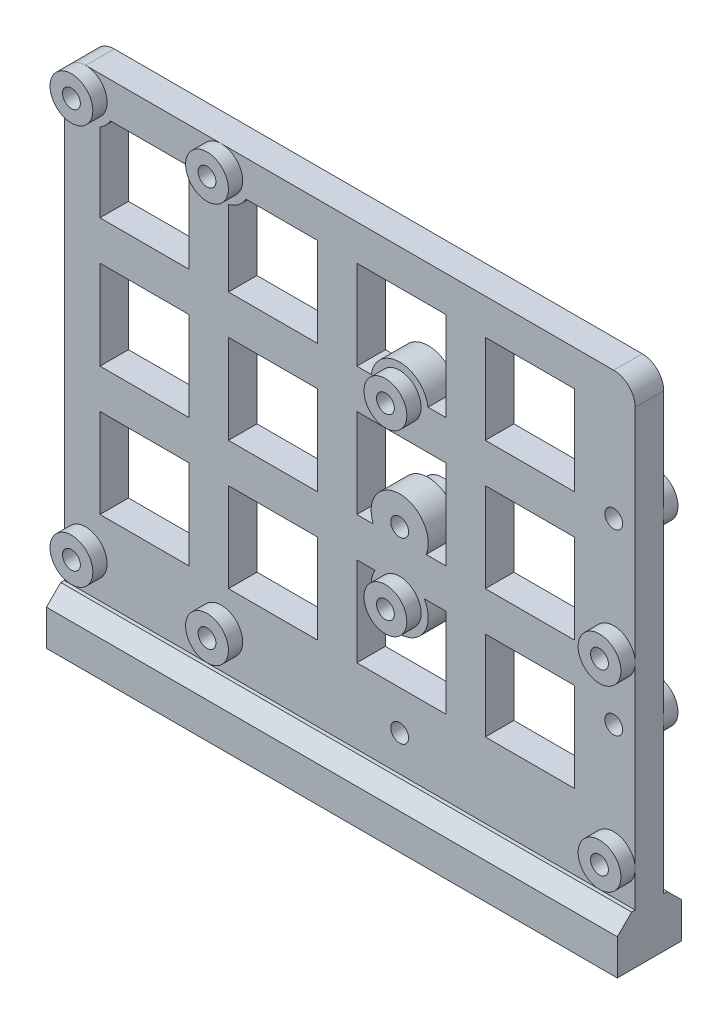
SolidWorks part; units mm, degrees
ref_plane "Спереди" through (0, 0, 0) normal (0, 0, 1) x (1, 0, 0)
ref_plane "Сверху" through (0, 0, 0) normal (0, 1, 0) x (1, 0, 0)
ref_plane "Справа" through (0, 0, 0) normal (1, 0, 0) x (0, 0, -1)
sketch "Sketch1" plane through (0, 0, 0) normal (0, 0, 1) x (1, 0, 0)
  line L1 (-12.5, 31) -> (12.5, 31)
  line L2 (-12.5, 31) -> (-12.5, -31)
  line L3 (-12.5, -31) -> (12.5, -31)
  line L4 (12.5, 31) -> (12.5, -31)
  line L5 (-12.5, 31) -> (12.5, -31) construction
  line L6 (-12.5, -31) -> (12.5, 31) construction
  line L48 (12.5, -31) -> (67.5, -31)
  line L49 (12.5, -31) -> (12.5, 31)
  line L50 (12.5, 31) -> (67.5, 31)
  line L51 (67.5, -31) -> (67.5, 31)
  dimension "D1" = 62
  dimension "D2" = 25
  dimension "D3" = 55
extrude "Boss-Extrude1" add sketch "Sketch1" along normal blind 4 contours L4 L1 L2 L3 | L48 L51 L50 L4
sketch "Sketch2" plane through (0, 0, 4) normal (0, 0, 1) x (1, 0, 0)
  line L0 (-4.7762, 0) -> (0, 0) construction
  line L1 (0, 0) -> (0, -10.2056) construction
  circle A0 centre (-9.5, -28) radius 1.25
  circle A1 centre (9.5, -28) radius 1.25
  circle A2 centre (9.5, 28) radius 1.25
  circle A3 centre (-9.5, 28) radius 1.25
  dimension "D1" = 2.5
  dimension "D3" = 19
  dimension "D2" = 56
extrude "Cut-Extrude1" cut sketch "Sketch2" against normal blind 4
sketch "Sketch3" plane through (0, 0, 4) normal (0, 0, 1) x (1, 0, 0)
  circle A0 centre (-9.5, 28) radius 3
  circle A1 centre (9.5, 28) radius 3
  circle A2 centre (-9.5, -28) radius 3
  circle A3 centre (9.5, -28) radius 3
  circle M3 centre (-9.5, 28) radius 1.25
  circle M4 centre (9.5, 28) radius 1.25
  circle M5 centre (9.5, -28) radius 1.25
  circle M6 centre (-9.5, -28) radius 1.25
  dimension "D1" = 6
  dimension "D2" = 6
  dimension "D3" = 6
  dimension "D4" = 6
extrude "Boss-Extrude2" add sketch "Sketch3" along normal blind 2 contours A0 M3 | A1 M4 | A2 M6 | A3 M5
sketch "Sketch4" plane through (0, 0, 4) normal (0, 0, 1) x (1, 0, 0)
  line L0 (67.5, -31) -> (67.5, 31) construction
  line L1 (9.5, -31) -> (67.5, -31) construction
  circle A0 centre (34.5, -12) radius 1.25
  circle A1 centre (64.5, -28) radius 1.25
  dimension "D1" = 2.5
  dimension "D2" = 2.5
  dimension "D3" = 30
  dimension "D4" = 16
  dimension "D6" = 3
  dimension "D5" = 3
extrude "Cut-Extrude2" cut sketch "Sketch4" against normal blind 10
sketch "Sketch5" plane through (0, 0, 4) normal (0, 0, 1) x (1, 0, 0)
  circle A0 centre (34.5, -12) radius 3
  circle A1 centre (64.5, -28) radius 3
  circle M1 centre (34.5, -12) radius 1.25
  circle M2 centre (64.5, -28) radius 1.25
  dimension "D1" = 6
  dimension "D2" = 6
extrude "Boss-Extrude3" add sketch "Sketch5" along normal blind 2 contours A0 M1 | A1 M2
pattern_linear "LPattern1" count 2 spacing 25 along (0, 1, 0) of "Boss-Extrude3", "Cut-Extrude2"
sketch "Sketch6" plane through (0, 0, 0) normal (0, 0, -1) x (-1, 0, 0)
  line L0 (-64.5, -28) -> (-64.5, 8.3618) construction
  line L1 (-34.5, -12) -> (-34.5, 19.7372) construction
  circle A0 centre (-64.5, -12) radius 1.25
  circle A1 centre (-34.5, -28) radius 1.25
  circle A2 centre (-34.5, -12) radius 1.25 construction
  circle A3 centre (-64.5, 13) radius 1.25
  circle A4 centre (-34.5, -3) radius 1.25
  circle A5 centre (-64.5, -3) radius 1.25 construction
  circle A6 centre (-34.5, 13) radius 1.25 construction
  dimension "D1" = 2.5
  dimension "D3" = 2.5
  dimension "D4" = 16
  dimension "D5" = 2.5
  dimension "D6" = 2.5
  dimension "D7" = 16
  dimension "D8" = 16
  dimension "D2" = 16
extrude "Cut-Extrude3" cut sketch "Sketch6" against normal through all
sketch "Sketch7" plane through (0, 0, 0) normal (0, 0, -1) x (-1, 0, 0)
  circle A0 centre (-64.5, -12) radius 3
  circle A1 centre (-34.5, -28) radius 3
  circle A2 centre (-64.5, 13) radius 3
  circle A3 centre (-34.5, -3) radius 3
  circle M1 centre (-64.5, -12) radius 1.25
  circle M2 centre (-34.5, -28) radius 1.25
  circle M3 centre (-64.5, 13) radius 1.25
  circle M4 centre (-34.5, -3) radius 1.25
  dimension "D1" = 6
  dimension "D2" = 6
  dimension "D3" = 6
  dimension "D4" = 6
extrude "Boss-Extrude4" add sketch "Sketch7" along normal blind 2 contours A2 M3 | A3 M4 | A1 M2 | A0 M1
sketch "Sketch8" plane through (0, 0, 4) normal (0, 0, 1) x (1, 0, 0)
  line L0 (-12.5, 28) -> (-12.5, -28) construction
  line L1 (-7.5, 26) -> (5, 26)
  line L2 (-7.5, 26) -> (-7.5, 13.5)
  line L3 (-7.5, 13.5) -> (5, 13.5)
  line L4 (5, 26) -> (5, 13.5)
  line L5 (-9.5, 31) -> (9.5, 31) construction
  line L6 (10.5, 26) -> (10.5, 13.5)
  line L7 (10.5, 26) -> (23, 26)
  line L8 (23, 26) -> (23, 13.5)
  line L9 (10.5, 13.5) -> (23, 13.5)
  line L10 (28.5, 26) -> (28.5, 13.5)
  line L11 (28.5, 26) -> (41, 26)
  line L12 (41, 26) -> (41, 13.5)
  line L13 (28.5, 13.5) -> (41, 13.5)
  line L14 (46.5, 26) -> (46.5, 13.5)
  line L15 (46.5, 26) -> (59, 26)
  line L16 (59, 26) -> (59, 13.5)
  line L17 (46.5, 13.5) -> (59, 13.5)
  line L18 (64.5, 26) -> (64.5, 13.5)
  line L19 (64.5, 26) -> (77, 26)
  line L20 (77, 26) -> (77, 13.5)
  line L21 (64.5, 13.5) -> (77, 13.5)
  line L22 (10.5, 8) -> (10.5, -4.5)
  line L23 (10.5, 8) -> (23, 8)
  line L24 (23, 8) -> (23, -4.5)
  line L25 (10.5, -4.5) -> (23, -4.5)
  line L26 (28.5, 8) -> (28.5, -4.5)
  line L27 (28.5, 8) -> (41, 8)
  line L28 (41, 8) -> (41, -4.5)
  line L29 (28.5, -4.5) -> (41, -4.5)
  line L30 (46.5, 8) -> (46.5, -4.5)
  line L31 (46.5, 8) -> (59, 8)
  line L32 (59, 8) -> (59, -4.5)
  line L33 (46.5, -4.5) -> (59, -4.5)
  line L34 (64.5, 8) -> (64.5, -4.5)
  line L35 (64.5, 8) -> (77, 8)
  line L36 (77, 8) -> (77, -4.5)
  line L37 (64.5, -4.5) -> (77, -4.5)
  line L38 (10.5, -10) -> (10.5, -22.5)
  line L39 (10.5, -10) -> (23, -10)
  line L40 (23, -10) -> (23, -22.5)
  line L41 (10.5, -22.5) -> (23, -22.5)
  line L42 (28.5, -10) -> (28.5, -22.5)
  line L43 (28.5, -10) -> (41, -10)
  line L44 (41, -10) -> (41, -22.5)
  line L45 (28.5, -22.5) -> (41, -22.5)
  line L46 (46.5, -10) -> (46.5, -22.5)
  line L47 (46.5, -10) -> (59, -10)
  line L48 (59, -10) -> (59, -22.5)
  line L49 (46.5, -22.5) -> (59, -22.5)
  line L50 (64.5, -10) -> (64.5, -22.5)
  line L51 (64.5, -10) -> (77, -10)
  line L52 (77, -10) -> (77, -22.5)
  line L53 (64.5, -22.5) -> (77, -22.5)
  line L54 (-7.5, 8) -> (-7.5, -4.5)
  line L55 (-7.5, 8) -> (5, 8)
  line L56 (5, 8) -> (5, -4.5)
  line L57 (-7.5, -4.5) -> (5, -4.5)
  line L58 (-7.5, -10) -> (-7.5, -22.5)
  line L59 (-7.5, -10) -> (5, -10)
  line L60 (5, -10) -> (5, -22.5)
  line L61 (-7.5, -22.5) -> (5, -22.5)
  line L62 (62.5, 26) -> (62.5, -22.5)
  line L63 (67.5, -3) -> (67.5, 31) construction
  circle A0 centre (34.5, -3) radius 4
  circle A1 centre (34.5, 13) radius 4
  circle A2 centre (34.5, -28) radius 4
  circle A3 centre (34.5, -12) radius 4
  circle A4 centre (-9.5, 28) radius 4
  circle A5 centre (9.5, 28) radius 4
  circle A6 centre (64.5, -3) radius 4
  circle A7 centre (64.5, 13) radius 4
  circle A8 centre (64.5, -12) radius 4
  dimension "D7" = 8
  dimension "D8" = 8
  dimension "D9" = 8
  dimension "D10" = 8
  dimension "D11" = 8
  dimension "D12" = 8
  dimension "D13" = 8
  dimension "D14" = 8
  dimension "D15" = 8
  dimension "D1" = 12.5
  dimension "D2" = 5
  dimension "D3" = 5
  dimension "D6" = 5
  dimension "D4" = 5
  dimension "D5" = 3
extrude "Cut-Extrude4" cut sketch "Sketch8" against normal through all contours L14 L17 L16 L15 | L30 L33 L32 L31 | L46 L49 L48 L47 | A3 L43 L42 L45 L44 | A0 L29 L28 L27 L26 | A1 L13 L12 L11 L10 | A5 L6 L9 L8 L7 | L22 L25 L24 L23 | L38 L41 L40 L39 | L58 L61 L60 L59 | L54 L57 L56 L55 | A4 L2 L3 L4 L1
fillet "Fillet1" radius 3 2 edges at (67.5, 31, 2) (-12.5, 31, 2)
sketch "Sketch9" plane through (0, -31, 0) normal (0, -1, 0) x (1, 0, 0)
  line L8 (-12.5, 0) -> (34.5, 0)
  line L9 (34.5, 0) -> (67.5, 0)
  line L10 (67.5, 0) -> (67.5, 4)
  line L11 (67.5, 4) -> (64.5, 4)
  line L12 (64.5, 4) -> (9.5, 4)
  line L13 (9.5, 4) -> (-9.5, 4)
  line L14 (-9.5, 4) -> (-12.5, 4)
  line L15 (-12.5, 4) -> (-12.5, 0)
  line L16 (-12.5, 0) -> (34.5, 0)
  line L17 (34.5, 0) -> (67.5, 0)
  line L18 (67.5, 0) -> (67.5, 4)
  line L19 (67.5, 4) -> (64.5, 4)
  line L20 (64.5, 4) -> (9.5, 4)
  line L21 (9.5, 4) -> (-9.5, 4)
  line L22 (-9.5, 4) -> (-12.5, 4)
  line L23 (-12.5, 4) -> (-12.5, 0)
  dimension "D1" = 0
extrude "Boss-Extrude5" add sketch "Sketch9" along normal blind 2
sketch "Sketch10" plane through (0, -33, 0) normal (0, -1, 0) x (1, 0, 0)
  line L0 (-12.5, 4) -> (-12.5, 0) construction
  line L1 (-12.5, -2.5) -> (67.5, -2.5)
  line L2 (-12.5, -2.5) -> (-12.5, 6.5)
  line L3 (-12.5, 6.5) -> (67.5, 6.5)
  line L4 (67.5, -2.5) -> (67.5, 6.5)
  line L5 (67.5, 0) -> (67.5, 4) construction
  line L6 (-12.5, 0) -> (67.5, 0) construction
  dimension "D1" = 9
  dimension "D2" = 2.5
extrude "Boss-Extrude6" add sketch "Sketch10" along normal blind 7
chamfer "Chamfer1" distance 2 angle 45 2 edges at (27.5, -33, 6.5) (27.5, -33, -2.5)
sketch "Sketch11" plane through (0, -40, 0) normal (0, -1, 0) x (1, 0, 0)
  line L0 (67.5, 2) -> (44.9408, 2) construction
  line L1 (67.5, -2.5) -> (67.5, 6.5) construction
  line L2 (27.5, 6.5) -> (27.5, 0) construction
  line L3 (67.5, 6.5) -> (-12.5, 6.5) construction
  circle A0 centre (60, 2) radius 1.45
  circle A1 centre (-5, 2) radius 1.45
  dimension "D1" = 2.9
  dimension "D2" = 7.5
extrude "Cut-Extrude5" cut sketch "Sketch11" against normal blind 7
